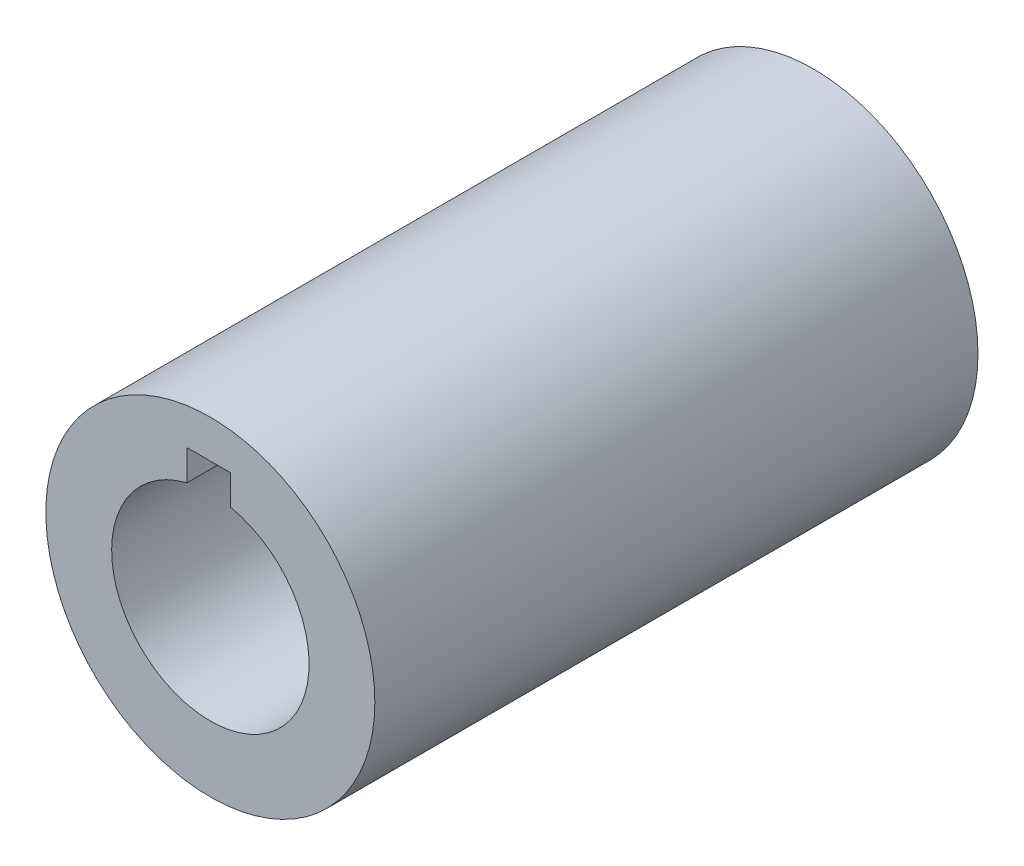
SolidWorks part; units mm, degrees
ref_plane "Front Plane" through (0, 0, 0) normal (0, 0, 1) x (1, 0, 0)
ref_plane "Top Plane" through (0, 0, 0) normal (0, 1, 0) x (1, 0, 0)
ref_plane "Right Plane" through (0, 0, 0) normal (1, 0, 0) x (0, 0, -1)
sketch "Sketch1" plane through (0, 0, 0) normal (0, 0, 1) x (1, 0, 0)
  line L0 (9.1428, -8.5113) -> (-8.8572, -8.5113) construction
  line L3 (2, 3.0164) -> (-2, 3.0164)
  line L4 (2, 3.0164) -> (2, 0.295)
  line L5 (-2, 3.0164) -> (-2, 0.2299)
  line L10 (0.1428, -8.5113) -> (0.1428, -17.5113) construction
  arc A0 (-2, 0.2299) -> (2, 0.295) centre (0.1428, -8.5113) ccw
  circle A1 centre (0.1428, -8.5113) radius 15
  dimension "D1" = 9
  dimension "D3" = 30
  dimension "D2" = 4
extrude "Boss-Extrude1" add sketch "Sketch1" along normal blind 55
